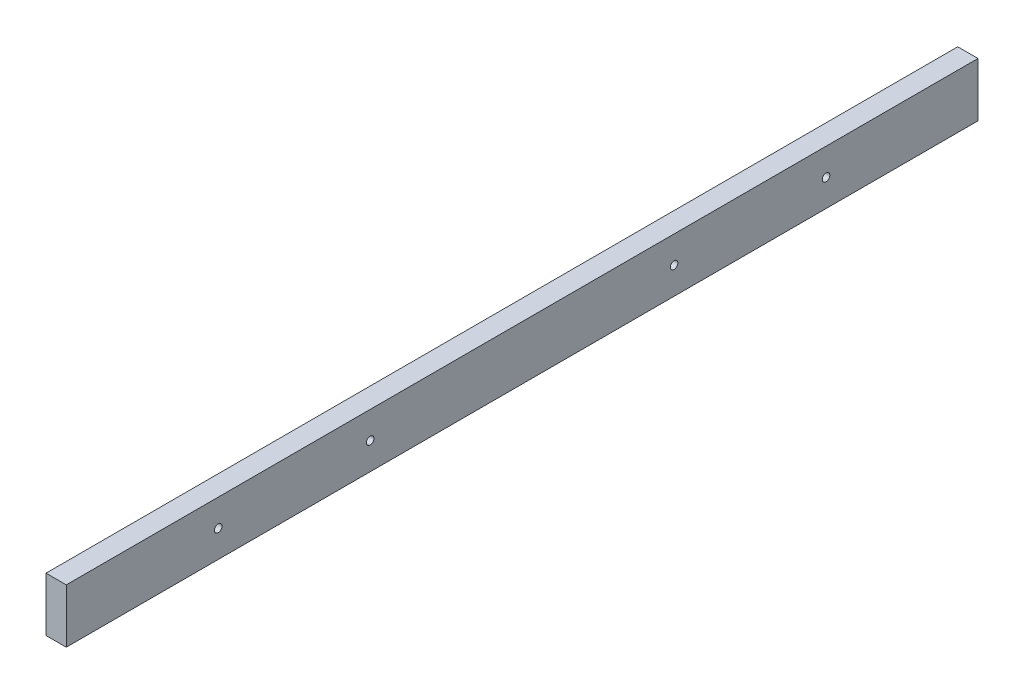
SolidWorks part; units mm, degrees
ref_plane "Front Plane" through (0, 0, 0) normal (0, 0, 1) x (1, 0, 0)
ref_plane "Top Plane" through (0, 0, 0) normal (0, 1, 0) x (1, 0, 0)
ref_plane "Right Plane" through (0, 0, 0) normal (1, 0, 0) x (0, 0, -1)
sketch "Sketch1" plane through (0, 0, 0) normal (0, 1, 0) x (1, 0, 0)
  line L0 (-3, 135) -> (3, 135)
  line L1 (-3, 135) -> (-3, -135)
  line L2 (-3, -135) -> (3, -135)
  line L3 (3, 135) -> (3, -135)
  line L4 (-3, 0) -> (3, 0) construction
  point P6 (0, 0)
extrude "Boss-Extrude1" add sketch "Sketch1" along normal blind 16
sketch "Sketch2" plane through (3, 0, 0) normal (1, 0, 0) x (0, 0, -1)
  line L0 (-135, 8) -> (-90, 8) construction
  line L1 (-135, 16) -> (-135, 0) construction
  line L2 (-90, 8) -> (-45, 8) construction
  line L3 (-45, 8) -> (0, 8) construction
  line L4 (0, 8) -> (45, 8) construction
  line L5 (45, 8) -> (90, 8) construction
  line L6 (90, 8) -> (135, 8) construction
  line L7 (135, 16) -> (135, 0) construction
  line L8 (0, 8) -> (0, 0) construction
  circle A0 centre (-90, 8) radius 1.125
  circle A2 centre (90, 8) radius 1.125
  circle A3 centre (-45, 8) radius 1.125
  circle A4 centre (45, 8) radius 1.125
  dimension "D1" = 2.25
extrude "Cut-Extrude1" cut sketch "Sketch2" against normal blind 10
